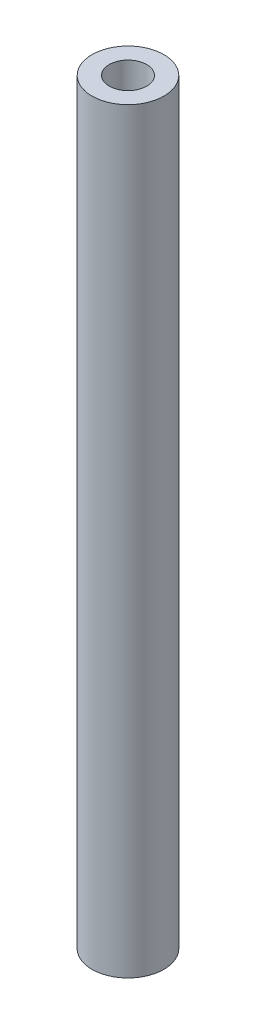
SolidWorks part; units mm, degrees
ref_plane "Front Plane" through (0, 0, 0) normal (0, 0, 1) x (1, 0, 0)
ref_plane "Top Plane" through (0, 0, 0) normal (0, 1, 0) x (1, 0, 0)
ref_plane "Right Plane" through (0, 0, 0) normal (1, 0, 0) x (0, 0, -1)
sketch "Sketch1" plane through (0, 0, 0) normal (0, 1, 0) x (1, 0, 0)
  circle A0 centre (0, 0) radius 6
  circle A1 centre (0, 0) radius 11.5
extrude "Boss-Extrude1" add sketch "Sketch1" along normal blind 242
